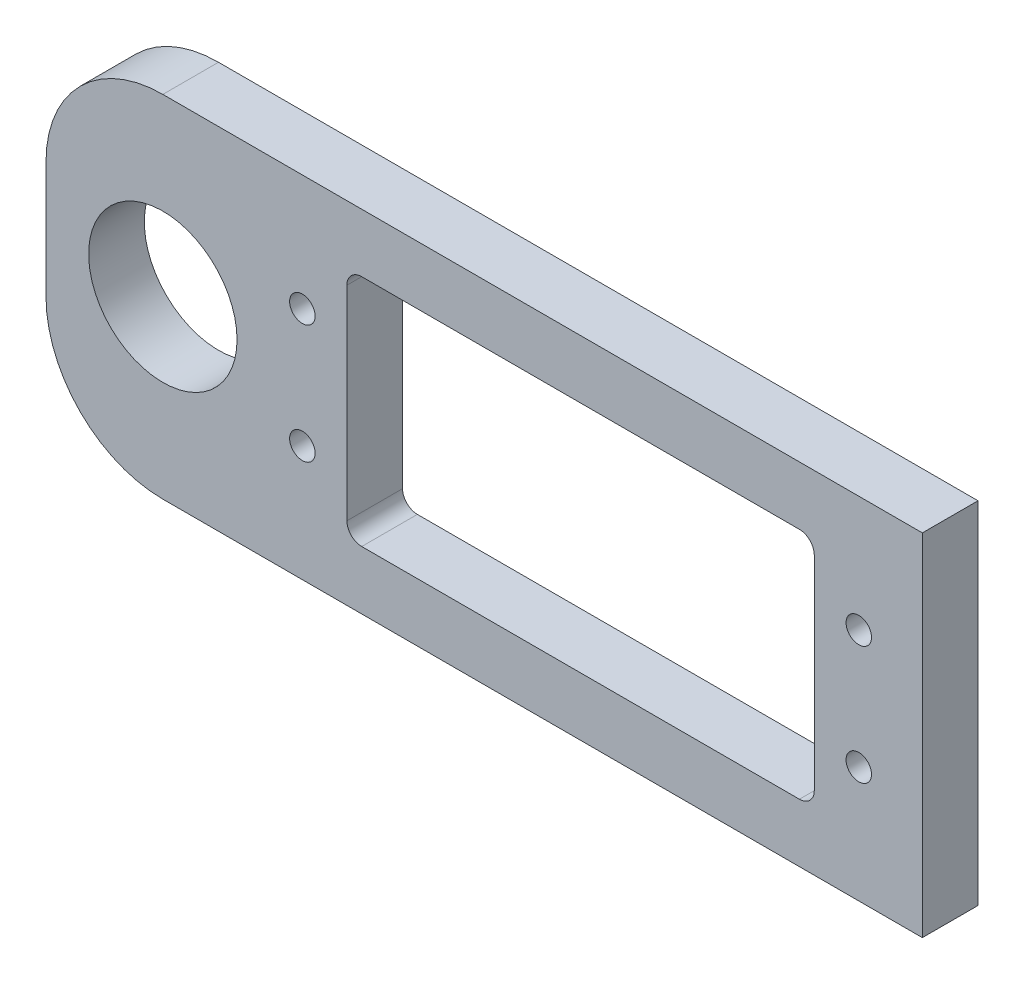
SolidWorks part; units mm, degrees
ref_plane "Front" through (0, 0, 0) normal (0, 0, 1) x (1, 0, 0)
ref_plane "Top" through (0, 0, 0) normal (0, 1, 0) x (1, 0, 0)
ref_plane "Right" through (0, 0, 0) normal (1, 0, 0) x (0, 0, -1)
sketch "Esquisse1" plane through (0, 0, 0) normal (0, 0, 1) x (1, 0, 0)
  line L1 (-37.5, 15) -> (37.5, 15)
  line L2 (-37.5, 15) -> (-37.5, -15)
  line L3 (-37.5, -15) -> (37.5, -15)
  line L4 (37.5, 15) -> (37.5, -15)
  line L5 (-37.5, 15) -> (37.5, -15) construction
  line L6 (-37.5, -15) -> (37.5, 15) construction
  point P0 (0, 0)
  dimension "D1" = 75
  dimension "D2" = 30
extrude "Boss.-Extru.1" add sketch "Esquisse1" along normal blind 4.7625
fillet "Congé1" radius 10 2 edges at (-37.5, -15, 2.3813) (-37.5, 15, 2.3813)
sketch "Esquisse2" plane through (0, 0, 4.7625) normal (0, 0, 1) x (1, 0, 0)
  line L0 (-37.5, 5) -> (-37.5, -5) construction
  line L1 (37.5, 15) -> (-27.5, 15) construction
  circle A0 centre (-27.5, 0) radius 6.35
  dimension "D1" = 10
  dimension "D2" = 12.7
  dimension "D3" = 15
extrude "Enlèv. mat.-Extru.1" cut sketch "Esquisse2" against normal blind 6
sketch "Esquisse5" plane through (0, 0, 4.7625) normal (0, 0, 1) x (1, 0, 0)
  line L2 (37.5, 15) -> (-27.5, 15) construction
  circle A0 centre (-2.1, 0) radius 3.5835 construction
  circle A1 centre (-27.5, 0) radius 6.35 construction
  dimension "D1" = 25.4
  dimension "D2" = 7.1671
  dimension "D3" = 15
sketch "Esquisse3" plane through (0, 0, 4.7625) normal (0, 0, 1) x (1, 0, 0)
  line L0 (37.5, 15) -> (-27.5, 15) construction
  line L1 (-11.75, 10) -> (28.25, 10)
  line L2 (-11.75, 10) -> (-11.75, -10)
  line L3 (-11.75, -10) -> (28.25, -10)
  line L4 (28.25, 10) -> (28.25, -10)
  circle A0 centre (-2.1, 0) radius 3.5835 construction
  dimension "D1" = 20
  dimension "D2" = 5
  dimension "D3" = 40
  dimension "D4" = 9.65
extrude "Enlèv. mat.-Extru.2" cut sketch "Esquisse3" against normal up to next
fillet "Congé2" radius 1.27 4 edges at (28.25, -10, 2.3813) (-11.75, -10, 2.3813) (28.25, 10, 2.3813) (-11.75, 10, 2.3813)
sketch "Esquisse4" plane through (0, 0, 4.7625) normal (0, 0, 1) x (1, 0, 0)
  line L0 (-11.75, 8.73) -> (-11.75, -8.73) construction
  line L1 (26.98, 10) -> (-10.48, 10) construction
  line L2 (50, 0) -> (-50, 0) construction
  line L4 (8.25, 10) -> (8.25, -10) construction
  line L5 (-10.48, -10) -> (26.98, -10) construction
  circle A0 centre (-15.56, 5.08) radius 1.09
  circle A1 centre (-15.56, -5.08) radius 1.09
  circle A2 centre (32.06, -5.08) radius 1.09
  circle A3 centre (32.06, 5.08) radius 1.09
  dimension "D3" = 2.18
  dimension "D1" = 3.81
  dimension "D2" = 4.92
extrude "Enlèv. mat.-Extru.3" cut sketch "Esquisse4" against normal up to next
